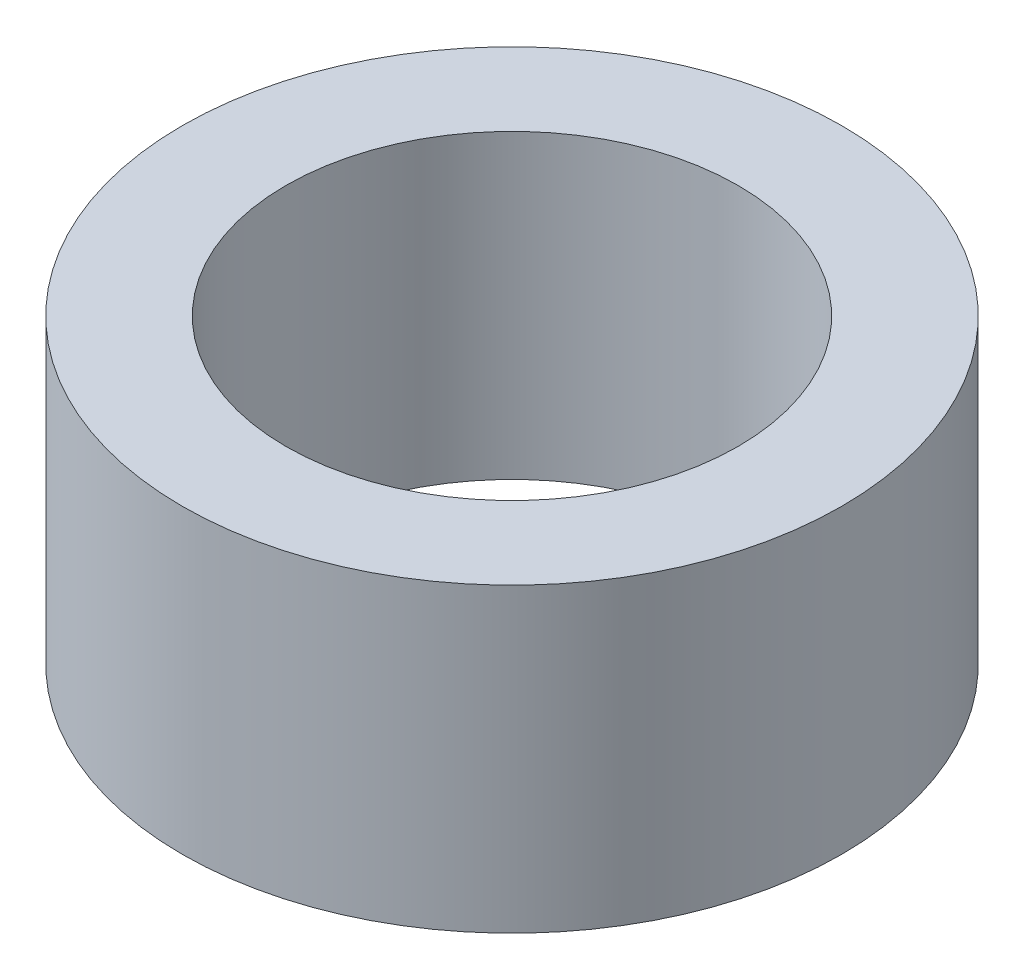
SolidWorks part; units mm, degrees
ref_plane "Front Plane" through (0, 0, 0) normal (0, 0, 1) x (1, 0, 0)
ref_plane "Top Plane" through (0, 0, 0) normal (0, 1, 0) x (1, 0, 0)
ref_plane "Right Plane" through (0, 0, 0) normal (1, 0, 0) x (0, 0, -1)
sketch "Sketch1" plane through (0, 0, 0) normal (0, 1, 0) x (1, 0, 0)
  circle A0 centre (0, 0) radius 11.1125
  dimension "D1" = 22.225
extrude "Boss-Extrude1" add sketch "Sketch1" along normal blind 10.16 contours A0
sketch "Sketch4" plane through (0, 10.16, 0) normal (0, 1, 0) x (1, 0, 0)
  circle A0 centre (0, 0) radius 7.62
  dimension "D1" = 15.24
extrude "Cut-Extrude1" cut sketch "Sketch4" against normal through all
sketch "Sketch5" plane through (0, 0, 0) normal (0, -1, 0) x (1, 0, 0)
